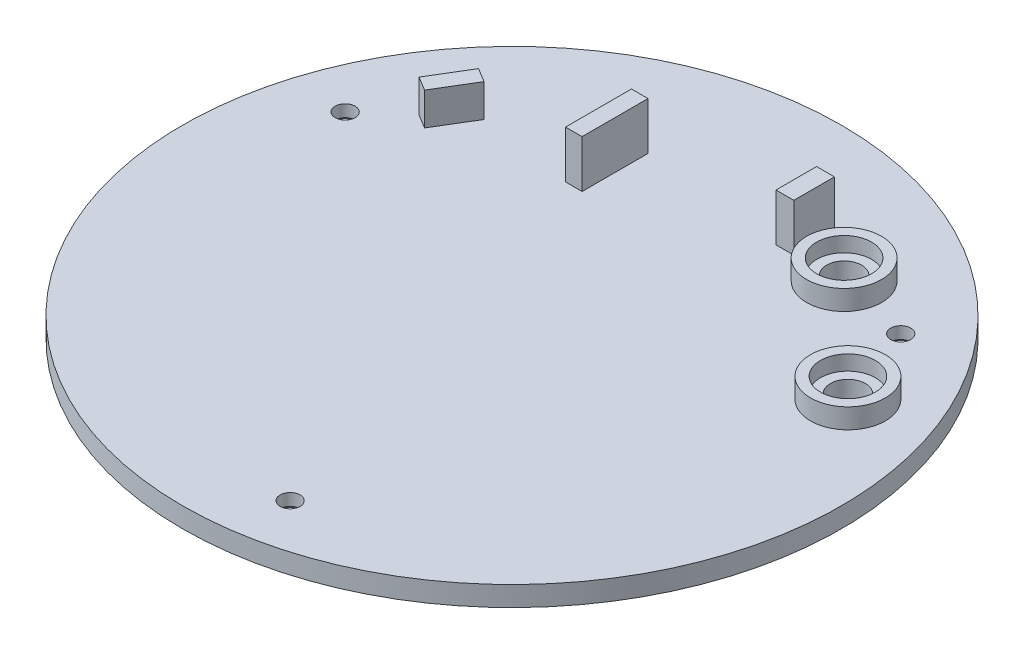
SolidWorks part; units mm, degrees
ref_plane "前视基准面" through (0, 0, 0) normal (0, 0, 1) x (1, 0, 0)
ref_plane "上视基准面" through (0, 0, 0) normal (0, 1, 0) x (1, 0, 0)
ref_plane "右视基准面" through (0, 0, 0) normal (1, 0, 0) x (0, 0, -1)
other "Configuration Table"
sketch "草图1" plane through (0, -12.25, 0) normal (0, -1, 0) x (1, 0, 0)
  circle A0 centre (0, 0) radius 33
extrude "凸台-拉伸1" add sketch "草图1" along normal blind 2
sketch "草图5" plane through (0, -12.25, 0) normal (0, 1, 0) x (1, 0, 0)
  line L10 (-8.8973, 14.2592) -> (-8.8973, 20.8632)
  line L11 (-8.8973, 14.2592) -> (-7.2413, 14.2592)
  line L12 (-8.8973, 20.8632) -> (-7.2413, 20.8632)
  line L13 (-7.2413, 14.2592) -> (-7.2413, 20.8632)
  line L14 (8.8827, 23.4032) -> (8.8827, 19.3392)
  line L15 (8.8827, 23.4032) -> (7.0956, 23.4032)
  line L16 (8.8827, 19.3392) -> (7.0956, 19.3392)
  line L17 (7.0956, 23.4032) -> (7.0956, 19.3392)
extrude "凸台-拉伸2" add sketch "草图5" along normal up to surface (4.76 mm away)
sketch "草图6" plane through (0, -12.25, 0) normal (0, 1, 0) x (1, 0, 0)
  line L0 (-22.047, 12.7335) -> (-19.8006, 16.4507)
  line L1 (-22.047, 12.7335) -> (-20.6377, 11.8818)
  line L2 (-19.8006, 16.4507) -> (-18.3913, 15.599)
  line L3 (-20.6377, 11.8818) -> (-18.3913, 15.599)
extrude "凸台-拉伸3" add sketch "草图6" along normal up to surface (3.2831 mm away)
sketch "草图8" plane through (0, -12.25, 0) normal (0, 1, 0) x (1, 0, 0)
  circle A1 centre (13.6355, 19.6206) radius 1.75 construction
  circle A2 centre (13.6355, 19.6206) radius 1.75
  circle A3 centre (24.0914, 9.5462) radius 1.75 construction
  circle A4 centre (24.0914, 9.5462) radius 1.75
  circle A7 centre (13.6355, 19.6206) radius 3.75
  circle A8 centre (24.0914, 9.5462) radius 3.75
  dimension "D1" = 2
extrude "凸台-拉伸4" add sketch "草图8" along normal blind 2
sketch "草图9" plane through (0, -14.25, 0) normal (0, -1, 0) x (1, 0, 0)
  circle A0 centre (24.0914, -9.5462) radius 1.75 construction
  circle A1 centre (13.6355, -19.6206) radius 1.75 construction
  circle A2 centre (24.0914, -9.5462) radius 1.75
  circle A3 centre (13.6355, -19.6206) radius 1.75
extrude "切除-拉伸3" cut sketch "草图9" against normal blind 2
sketch "草图10" plane through (0, -10.25, 0) normal (0, 1, 0) x (1, 0, 0)
  circle A0 centre (13.6355, 19.6206) radius 1.75 construction
  circle A1 centre (13.6355, 19.6206) radius 1.75
extrude "切除-拉伸-薄壁1" cut sketch "草图10" against normal blind 1.5 thin
sketch "草图11" plane through (0, -10.25, 0) normal (0, 1, 0) x (1, 0, 0)
  circle A0 centre (24.0914, 9.5462) radius 1.75 construction
  circle A3 centre (24.0914, 9.5462) radius 1.75
extrude "切除-拉伸-薄壁2" cut sketch "草图11" against normal blind 1.5 thin
sketch "草图12" plane through (0, -14.25, 0) normal (0, -1, 0) x (1, 0, 0)
  circle A0 centre (-26.0035, -9.2966) radius 1
  circle A2 centre (4.9507, 27.1679) radius 1
  circle A4 centre (21.0528, -17.8714) radius 1
  point P13 (0, 0)
  dimension "D1" = 3
extrude "切除-拉伸4" cut sketch "草图12" against normal blind 2
sketch "草图13" plane through (0, -14.25, 0) normal (0, -1, 0) x (1, 0, 0)
  circle A0 centre (4.9507, 27.1679) radius 2
  circle A1 centre (21.0528, -17.8714) radius 2
  circle A2 centre (-26.0035, -9.2966) radius 2
  point P10 (0, 0)
  dimension "D1" = 3
extrude "切除-拉伸-薄壁3" cut sketch "草图13" against normal blind 0.8 thin thin type one direction reverse wall 1
